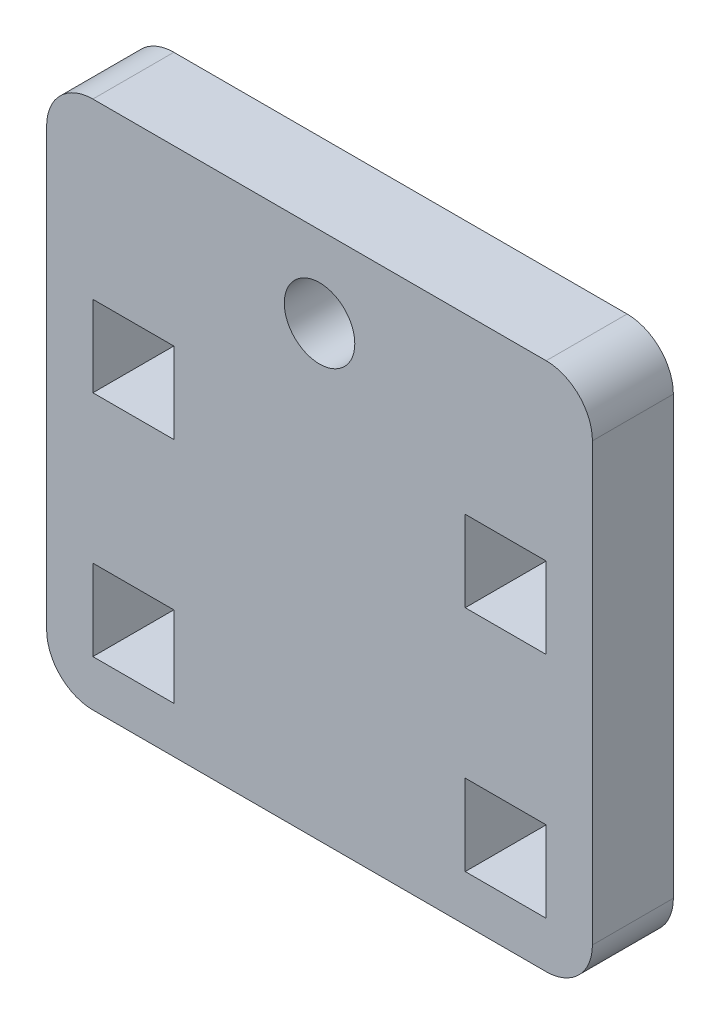
SolidWorks part; units mm, degrees
material "Balsa"
ref_plane "Front Plane" through (0, 0, 0) normal (0, 0, 1) x (1, 0, 0)
ref_plane "Top Plane" through (0, 0, 0) normal (0, 1, 0) x (1, 0, 0)
ref_plane "Right Plane" through (0, 0, 0) normal (1, 0, 0) x (0, 0, -1)
sketch "Sketch1" plane through (0, 0, 0) normal (0, 0, 1) x (1, 0, 0)
  line L0 (0, -6.9855) -> (0, 22.204) construction
  line L1 (-11.8, 0) -> (11.8, 0)
  line L2 (-11.8, 0) -> (-11.8, 22.88)
  line L4 (11.8, 0) -> (11.8, 22.88)
  line L5 (-7.1026, 8.69) -> (6.6682, 8.69) construction
  line L6 (-9.8, 2) -> (-6.3, 2)
  line L7 (-9.8, 2) -> (-9.8, 5.5)
  line L8 (-9.8, 5.5) -> (-6.3, 5.5)
  line L9 (-6.3, 2) -> (-6.3, 5.5)
  line L10 (6.3, 2) -> (9.8, 2)
  line L11 (6.3, 2) -> (6.3, 5.5)
  line L12 (6.3, 5.5) -> (9.8, 5.5)
  line L13 (9.8, 2) -> (9.8, 5.5)
  line L14 (6.3, 15.38) -> (6.3, 11.88)
  line L15 (6.3, 11.88) -> (9.8, 11.88)
  line L16 (9.8, 15.38) -> (9.8, 11.88)
  line L17 (6.3, 15.38) -> (9.8, 15.38)
  line L18 (-9.8, 15.38) -> (-6.3, 15.38)
  line L19 (-9.8, 15.38) -> (-9.8, 11.88)
  line L20 (-9.8, 11.88) -> (-6.3, 11.88)
  line L21 (-6.3, 15.38) -> (-6.3, 11.88)
  line L25 (-11.8, 22.88) -> (11.8, 22.88)
  circle A0 centre (0, 19.38) radius 1.525
  point P11 (0, 0)
  dimension "D8" = 3.05
  dimension "D1" = 23.6
  dimension "D2" = 22.88
  dimension "D3" = 2
  dimension "D4" = 2
  dimension "D5" = 3.5
  dimension "D6" = 2
  dimension "D7" = 3.19
  dimension "D11" = 4
extrude "Boss-Extrude1" add sketch "Sketch1" along normal blind 3.5
fillet "Fillet1" radius 2 4 edges at (-11.8, 0, 1.75) (11.8, 0, 1.75) (11.8, 22.88, 1.75) (-11.8, 22.88, 1.75)
